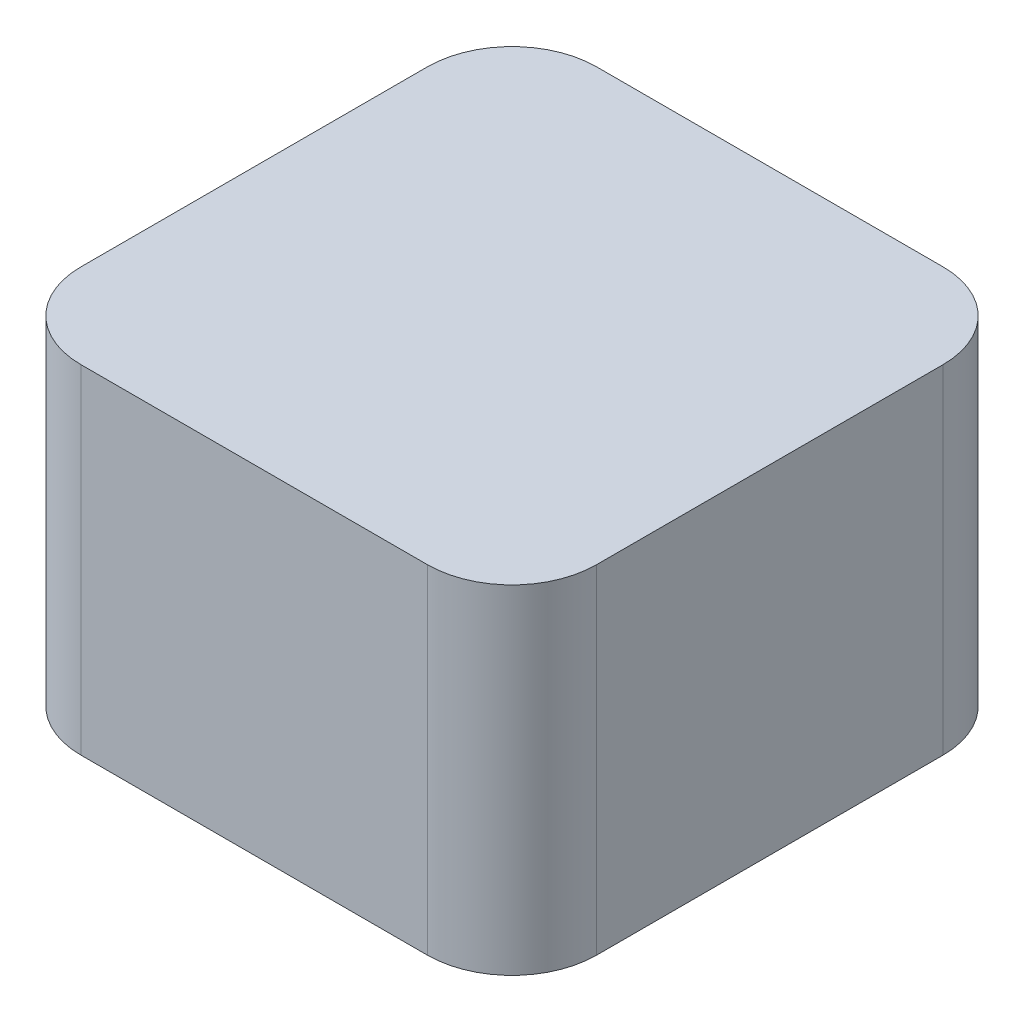
SolidWorks part; units mm, degrees
ref_plane "Front Plane" through (0, 0, 0) normal (0, 0, 1) x (1, 0, 0)
ref_plane "Top Plane" through (0, 0, 0) normal (0, 1, 0) x (1, 0, 0)
ref_plane "Right Plane" through (0, 0, 0) normal (1, 0, 0) x (0, 0, -1)
sketch "Sketch1" plane through (0, 0, 0) normal (0, 1, 0) x (1, 0, 0)
  line L1 (-4.1, 6.1) -> (4.1, 6.1)
  line L2 (-6.1, 4.1) -> (-6.1, -4.1)
  line L3 (-4.1, -6.1) -> (4.1, -6.1)
  line L4 (6.1, 4.1) -> (6.1, -4.1)
  arc A0 (4.1, 6.1) -> (6.1, 4.1) centre (4.1, 4.1) cw
  arc A1 (6.1, -4.1) -> (4.1, -6.1) centre (4.1, -4.1) cw
  arc A2 (-4.1, -6.1) -> (-6.1, -4.1) centre (-4.1, -4.1) cw
  arc A3 (-6.1, 4.1) -> (-4.1, 6.1) centre (-4.1, 4.1) cw
  point P4 (0, -6.1)
  point P6 (-6.1, 0)
  point P9 (6.1, 6.1)
  point P12 (6.1, -6.1)
  point P15 (-6.1, -6.1)
  dimension "D3" = 2
  dimension "D1" = 12.2
  dimension "D2" = 12.2
extrude "Boss-Extrude1" add sketch "Sketch1" along normal blind 8
